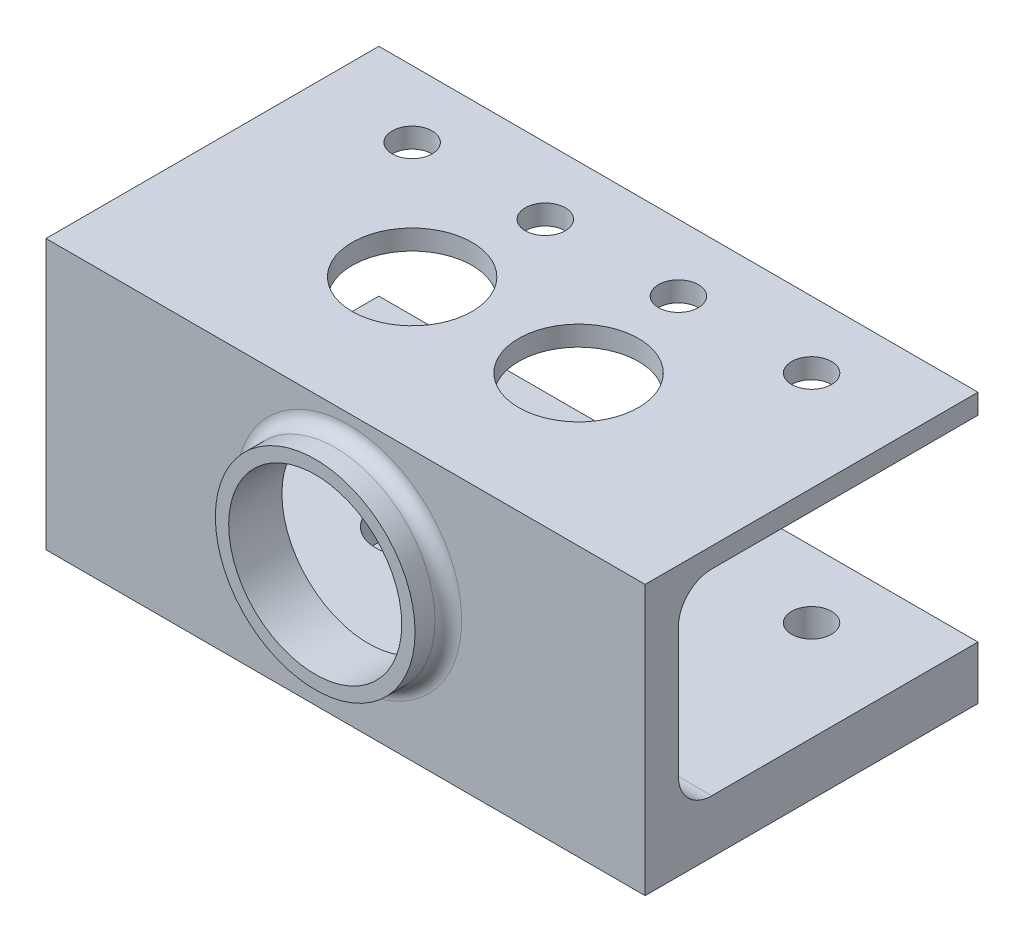
SolidWorks part; units mm, degrees
ref_plane "Спереди" through (0, 0, 0) normal (0, 0, 1) x (1, 0, 0)
ref_plane "Сверху" through (0, 0, 0) normal (0, 1, 0) x (1, 0, 0)
ref_plane "Справа" through (0, 0, 0) normal (1, 0, 0) x (0, 0, -1)
sketch "Sketch2" plane through (0, 0, 0) normal (0, 1, 0) x (1, 0, 0)
  line L1 (-45, 22.5) -> (45, 22.5)
  line L2 (-45, 22.5) -> (-45, -22.5)
  line L3 (-45, -22.5) -> (45, -22.5)
  line L4 (45, 22.5) -> (45, -22.5)
  line L5 (-45, 22.5) -> (45, -22.5) construction
  line L6 (-45, -22.5) -> (45, 22.5) construction
  point P0 (0, 0)
  dimension "D1" = 45
  dimension "D2" = 90
extrude "Boss-Extrude1" add sketch "Sketch2" along normal blind 8
sketch "Sketch3" plane through (0, 8, 0) normal (0, 1, 0) x (1, 0, 0)
  line L0 (0, 0) -> (0, 9.7627) construction
  circle A0 centre (12.5, 0) radius 3.25
  circle A1 centre (-12.5, 0) radius 3.25
  dimension "D1" = 6.5
  dimension "D2" = 25
extrude "Cut-Extrude1" cut sketch "Sketch3" against normal blind 10
sketch "Sketch5" plane through (0, 8, 0) normal (0, 1, 0) x (1, 0, 0)
  circle A0 centre (-12.5, 0) radius 5.5
  circle A1 centre (12.5, 0) radius 5.5
  dimension "D1" = 11
extrude "Cut-Extrude2" cut sketch "Sketch5" against normal blind 5
sketch "Sketch6" plane through (0, 8, 0) normal (0, 1, 0) x (1, 0, 0)
  line L0 (45, -22.5) -> (45, 22.5) construction
  line L1 (-45, -22.5) -> (45, -22.5)
  line L2 (-45, -22.5) -> (-45, -17.5)
  line L3 (-45, -17.5) -> (45, -17.5)
  line L4 (45, -22.5) -> (45, -17.5)
  dimension "D1" = 5
extrude "Boss-Extrude2" add sketch "Sketch6" along normal blind 32.5
sketch "Sketch7" plane through (0, 0, 17.5) normal (0, 0, -1) x (-1, 0, 0)
  line L0 (45, 40.5) -> (45, 8) construction
  line L1 (-45, 40.5) -> (45, 40.5)
  line L2 (-45, 40.5) -> (-45, 37.5)
  line L3 (-45, 37.5) -> (45, 37.5)
  line L4 (45, 40.5) -> (45, 37.5)
  dimension "D1" = 3
extrude "Boss-Extrude3" add sketch "Sketch7" along normal blind 45
sketch "Sketch8" plane through (0, 0, 22.5) normal (0, 0, 1) x (1, 0, 0)
  line L1 (-45, 37.5) -> (45, 37.5)
  line L2 (-45, 37.5) -> (-45, 8)
  line L3 (-45, 8) -> (45, 8)
  line L4 (45, 37.5) -> (45, 8)
  line L9 (-26.8328, 7.5246) -> (27.7126, 36.5) construction
  line L10 (-26.8328, 36.5) -> (27.7126, 7.5246) construction
  circle A1 centre (0.4399, 22.0123) radius 13
extrude "Cut-Extrude4" cut sketch "Sketch8" against normal blind 13 contours A1
sketch "Sketch11" plane through (0, 0, 22.5) normal (0, 0, 1) x (1, 0, 0)
  circle A0 centre (0.4399, 22.0123) radius 13
  circle A1 centre (0.4399, 22.0123) radius 15
  dimension "D1" = 2
extrude "Boss-Extrude6" add sketch "Sketch11" along normal blind 5
fillet "Fillet1" radius 2 1 edges at (-14.5601, 22.0123, 22.5)
sketch "Sketch12" plane through (0, 0, 17.5) normal (0, 0, -1) x (-1, 0, 0)
  line L5 (-45, 37.5) -> (45, 37.5) construction
  line L6 (-27.8462, 7.5246) -> (26.9664, 7.5246)
  line L7 (-27.8462, 7.5246) -> (-27.8462, 37.5)
  line L8 (-27.8462, 37.5) -> (26.9664, 37.5)
  line L9 (26.9664, 7.5246) -> (26.9664, 37.5)
  line L10 (-27.8462, 7.5246) -> (26.9664, 37.5) construction
  line L11 (-27.8462, 37.5) -> (26.9664, 7.5246) construction
  circle A0 centre (-0.4399, 22.5123) radius 31.2368
  point P0 (-0.4399, 22.0123)
  circle M6 centre (-0.4399, 22.0123) radius 13
  line M7 (45, 37.5) -> (-45, 37.5)
  line M9 (-45, 8) -> (45, 8)
extrude "Cut-Extrude5" cut sketch "Sketch12" against normal blind 2 contours L9 L7 M9 M7 M6 | L7 A0 M9 | A0 L9 M9
sketch "Sketch13" plane through (0, 40.5, 0) normal (0, 1, 0) x (1, 0, 0)
  line L0 (-45, 27.5) -> (-45, -22.5) construction
  line L1 (-26.9664, -17.5) -> (-45, -17.5) construction
  circle A0 centre (-30, 17.5) radius 3
  circle A1 centre (-10, 17.5) radius 3
  circle A2 centre (10, 17.5) radius 3
  circle A3 centre (30, 17.5) radius 3
  dimension "D2" = 15
  dimension "D3" = 35
  dimension "D4" = 6
  dimension "D1" = 4
extrude "Cut-Extrude6" cut sketch "Sketch13" against normal through all both and the other way through all
sketch "Sketch14" plane through (0, 40.5, 0) normal (0, 1, 0) x (1, 0, 0)
  circle A0 centre (-12.5, 0) radius 9
  circle A1 centre (12.5, 0) radius 9
  dimension "D1" = 18
extrude "Cut-Extrude7" cut sketch "Sketch14" against normal blind 12
sketch "Sketch16" plane through (0, 0, -22.5) normal (0, 0, -1) x (-1, 0, 0)
  line L1 (-45, 8) -> (45, 8)
  line L2 (-45, 8) -> (-45, 0)
  line L3 (-45, 0) -> (45, 0)
  line L4 (45, 8) -> (45, 0)
extrude "Boss-Extrude7" add sketch "Sketch16" along normal blind 5
fillet "Fillet2" radius 5 4 edges at (36.5504, 8, 17.5) (-36.1106, 8, 17.5) (36.4231, 37.5, 17.5) (-35.9832, 37.5, 17.5)
